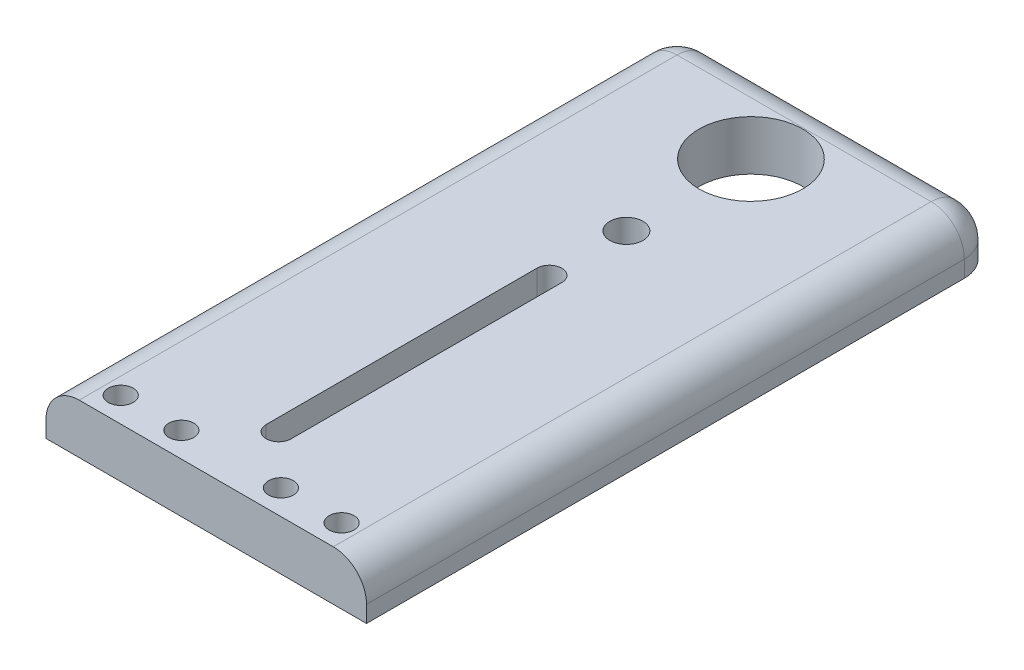
SolidWorks part; units mm, degrees
ref_plane "Front" through (0, 0, 0) normal (0, 0, 1) x (1, 0, 0)
ref_plane "Top" through (0, 0, 0) normal (0, 1, 0) x (1, 0, 0)
ref_plane "Right" through (0, 0, 0) normal (1, 0, 0) x (0, 0, -1)
sketch "Sketch1" plane through (0, 0, 0) normal (0, 1, 0) x (1, 0, 0)
  line L1 (24.511, -48.26) -> (-24.511, -48.26)
  line L2 (24.511, -48.26) -> (24.511, 48.26)
  line L3 (24.511, 48.26) -> (-24.511, 48.26)
  line L4 (-24.511, -48.26) -> (-24.511, 48.26)
  line L5 (24.511, -48.26) -> (-24.511, 48.26) construction
  line L6 (24.511, 48.26) -> (-24.511, -48.26) construction
  point P0 (0, 0)
  dimension "D1" = 49.022
  dimension "D2" = 96.52
extrude "Boss-Extrude1" add sketch "Sketch1" along normal blind 7.62
sketch "Sketch2" plane through (0, 7.62, 0) normal (0, 1, 0) x (1, 0, 0)
  line L0 (0, 0) -> (0, -48.26) construction
  line L1 (-24.511, -48.26) -> (24.511, -48.26) construction
  line L2 (-24.511, -44.45) -> (24.511, -44.45) construction
  line L3 (-24.511, 48.26) -> (-24.511, -48.26) construction
  line L4 (24.511, -48.26) -> (24.511, 48.26) construction
  circle A0 centre (-16.891, -44.45) radius 1.905
  circle A1 centre (-7.62, -44.45) radius 1.905
  circle A2 centre (7.62, -44.45) radius 1.905
  circle A3 centre (16.891, -44.45) radius 1.905
  dimension "D2" = 3.81
  dimension "D3" = 3.81
  dimension "D4" = 3.81
  dimension "D5" = 3.81
  dimension "D1" = 3.81
  dimension "D6" = 7.62
  dimension "D7" = 7.62
  dimension "D8" = 7.62
  dimension "D9" = 7.62
extrude "Cut-Extrude1" cut sketch "Sketch2" against normal through all contours A0 | A1 | A2 | A3
sketch "Sketch3" plane through (0, 7.62, 0) normal (0, 1, 0) x (1, 0, 0)
  line L0 (-24.511, 35.052) -> (24.511, 35.052) construction
  line L1 (-24.511, 48.26) -> (-24.511, -48.26) construction
  line L2 (24.511, -48.26) -> (24.511, 48.26) construction
  line L3 (-24.511, -48.26) -> (24.511, -48.26) construction
  line L4 (0, 0) -> (0, 48.26) construction
  line L5 (24.511, 48.26) -> (-24.511, 48.26) construction
  circle A0 centre (0, 35.052) radius 7.9375
  dimension "D2" = 15.875
  dimension "D1" = 83.312
extrude "Cut-Extrude2" cut sketch "Sketch3" against normal through all
fillet "Fillet1" radius 5.08 2 edges at (-24.511, 3.81, -48.26) (24.511, 3.81, -48.26)
fillet "Fillet2" radius 5.08 5 edges at (-24.511, 7.62, 2.54) (-23.0231, 7.62, -46.7721) (0, 7.62, -48.26) (23.0231, 7.62, -46.7721) (24.511, 7.62, 2.54)
sketch "Sketch4" plane through (0, 7.62, 0) normal (0, 1, 0) x (1, 0, 0)
  line L0 (0, -48.26) -> (0, 5.7668) construction
  line L1 (-19.431, -48.26) -> (19.431, -48.26) construction
  line L3 (-1.905, -34.6458) -> (-1.905, -37.1858)
  line L5 (-1.905, -34.6458) -> (-1.905, 4.217)
  line L7 (1.905, -34.6458) -> (1.905, 4.217)
  line L8 (-1.905, -34.6458) -> (0.865, 5.9745) construction
  line L9 (-1.0874, 9.236) -> (-0.9807, 7.6718) construction
  line L11 (1.905, -37.1858) -> (1.905, -34.6458)
  line L12 (0.9807, 7.6718) -> (1.0874, 9.236) construction
  line L13 (-0.7451, 4.217) -> (0.7451, 4.217) construction
  line L14 (-0.865, 5.9745) -> (1.905, -34.6458) construction
  arc A2 (-1.905, -37.1858) -> (1.905, -37.1858) centre (0, -37.1858) ccw
  arc A4 (0.8032, 5.9444) -> (0.865, 5.9745) centre (0, 7.6718) ccw
  arc A6 (1.905, 4.217) -> (-1.905, 4.217) centre (0, 4.217) ccw
  point P6 (0, -6.7099)
  dimension "D3" = 3.81
  dimension "D4" = 2.54
extrude "Cut-Extrude3" cut sketch "Sketch4" against normal through all
sketch "Sketch5" plane through (0, 7.62, 0) normal (0, 1, 0) x (1, 0, 0)
  line L0 (0, 35.052) -> (0, 16.002) construction
  circle A0 centre (0, 35.052) radius 7.9375 construction
  circle A1 centre (0, 35.052) radius 7.9375
  circle A2 centre (0, 35.052) radius 5.3594 construction
  circle A4 centre (0, 16.002) radius 2.54
  dimension "D1" = 10.7188
  dimension "D2" = 19.05
  dimension "D3" = 5.08
extrude "Cut-Extrude4" cut sketch "Sketch5" against normal through all
